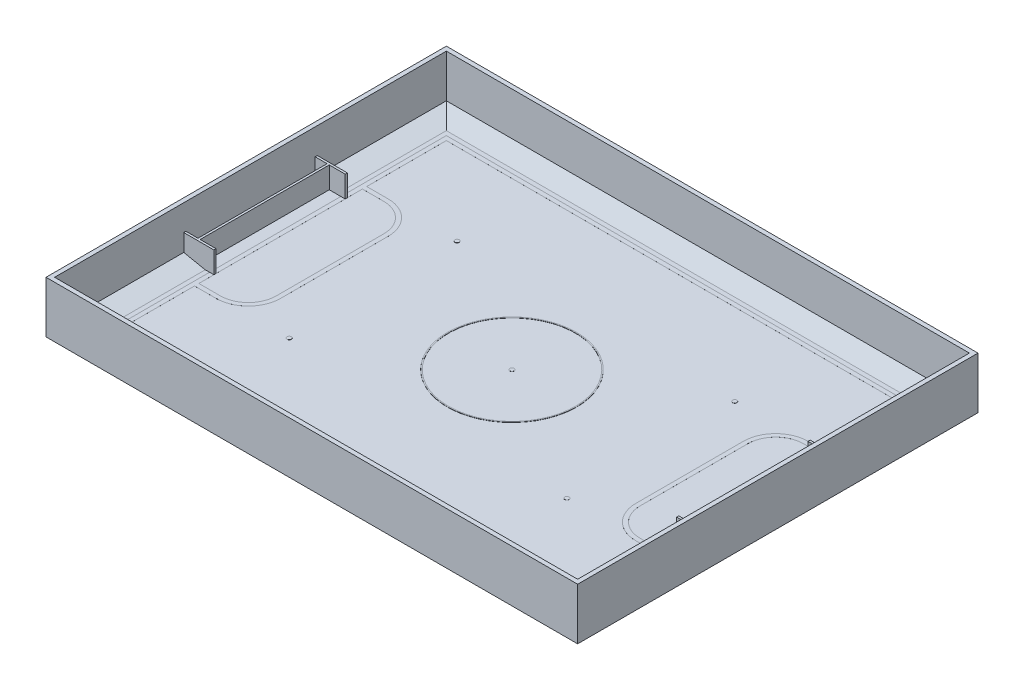
SolidWorks part; units mm, degrees
ref_plane "Alzado" through (0, 0, 0) normal (0, 0, 1) x (1, 0, 0)
ref_plane "Planta" through (0, 0, 0) normal (0, 1, 0) x (1, 0, 0)
ref_plane "Vista lateral" through (0, 0, 0) normal (1, 0, 0) x (0, 0, -1)
sketch "Croquis1" plane through (0, 0, 0) normal (0, 1, 0) x (1, 0, 0)
  line L0 (0, 0) -> (0, 182)
  line L1 (0, 182) -> (243, 182)
  line L2 (243, 182) -> (243, 0)
  line L3 (243, 0) -> (0, 0)
  line L4 (245, -2) -> (-2, -2)
  line L5 (-2, -2) -> (-2, 184)
  line L6 (-2, 184) -> (245, 184)
  line L7 (245, 184) -> (245, -2)
  dimension "D1" = 182
  dimension "D2" = 243
  dimension "D3" = 2
extrude "Wall" add sketch "Croquis1" along normal blind 24
sketch "Croquis4" plane through (0, 0, 0) normal (0, 1, 0) x (1, 0, 0)
  line L1 (243, 182) -> (0, 182)
  line L2 (243, 182) -> (243, 0)
  line L3 (243, 0) -> (0, 0)
  line L4 (0, 182) -> (0, 0)
extrude "Field" add sketch "Croquis4" along normal blind 2
sketch "Croquis5" plane through (0, 2, 0) normal (0, 1, 0) x (1, 0, 0)
  line L0 (243, 0) -> (231, 0) construction
  line L1 (0, 0) -> (243, 0) construction
  line L2 (231, 0) -> (231, 12) construction
  line L3 (231, 12) -> (12, 12)
  line L4 (12, 12) -> (12, 170)
  line L5 (12, 170) -> (231, 170)
  line L6 (231, 170) -> (231, 12)
  line L7 (229, 0) -> (229, 12)
  line L8 (229, 14) -> (14, 14)
  line L9 (14, 14) -> (14, 51)
  line L10 (14, 168) -> (229, 168)
  line L11 (229, 168) -> (229, 131)
  line L12 (229, 91) -> (204, 91) construction
  line L13 (204, 91) -> (204, 66)
  line L14 (219, 51) -> (229, 51)
  line L15 (204, 91) -> (206, 91) construction
  line L16 (219, 53) -> (229, 53)
  line L17 (206, 89) -> (206, 66)
  line L18 (206, 89) -> (206, 89)
  line L19 (206, 89) -> (206, 93)
  line L20 (121.5, 168) -> (121.5, 14) construction
  line L21 (204, 91) -> (206, 91) construction
  line L22 (206, 93) -> (206, 116)
  line L23 (219, 129) -> (229, 129)
  line L24 (219, 131) -> (229, 131)
  line L25 (204, 91) -> (204, 116)
  line L26 (39, 91) -> (37, 91) construction
  line L27 (39, 91) -> (37, 91) construction
  line L28 (14, 91) -> (39, 91) construction
  line L29 (39, 91) -> (39, 116)
  line L30 (24, 131) -> (14, 131)
  line L31 (24, 129) -> (14, 129)
  line L32 (37, 93) -> (37, 116)
  line L33 (37, 89) -> (37, 93)
  line L34 (37, 89) -> (37, 66)
  line L35 (24, 53) -> (14, 53)
  line L36 (24, 51) -> (14, 51)
  line L37 (39, 91) -> (39, 66)
  line L38 (14, 53) -> (14, 129)
  line L39 (14, 131) -> (14, 168)
  line L40 (14, 14) -> (14, 168) construction
  line L41 (229, 51) -> (229, 14)
  line L42 (229, 129) -> (229, 53)
  line L43 (229, 168) -> (229, 14) construction
  arc A0 (219, 51) -> (204, 66) centre (219, 66) cw
  arc A1 (219, 53) -> (206, 66) centre (219, 66) cw
  arc A2 (219, 129) -> (206, 116) centre (219, 116) ccw
  arc A3 (219, 131) -> (204, 116) centre (219, 116) ccw
  arc A4 (24, 131) -> (39, 116) centre (24, 116) cw
  arc A5 (24, 129) -> (37, 116) centre (24, 116) cw
  arc A6 (24, 53) -> (37, 66) centre (24, 66) ccw
  arc A7 (24, 51) -> (39, 66) centre (24, 66) ccw
  point P21 (204, 51)
  point P31 (204, 131)
  point P43 (39, 131)
  point P54 (39, 51)
  dimension "D8" = 15
  dimension "D1" = 158
  dimension "D2" = 219
  dimension "D3" = 12
  dimension "D4" = 12
  dimension "D5" = 2
  dimension "D6" = 40
  dimension "D7" = 25
  dimension "D9" = 2
extrude "WhiteLine" add sketch "Croquis5" along normal blind 0.01 contours L6 L5 L4 L3 L10 L11 L8 L9
sketch "Croquis6" plane through (0, 2, 0) normal (0, 1, 0) x (1, 0, 0)
  line L0 (14, 91) -> (229, 91) construction
  line L1 (14, 53) -> (14, 129) construction
  line L2 (229, 129) -> (229, 53) construction
  line L3 (12, 170) -> (57, 170) construction
  line L4 (12, 170) -> (231, 170) construction
  line L5 (57, 170) -> (57, 130) construction
  line L6 (14, 168) -> (229, 168) construction
  line L7 (121.5, 168) -> (121.5, 14) construction
  line L8 (229, 14) -> (14, 14) construction
  circle A0 centre (121.5, 91) radius 30
  circle A1 centre (121.5, 91) radius 29.5
  circle A2 centre (57, 130) radius 1
  circle A3 centre (57, 52) radius 1
  circle A4 centre (186, 52) radius 1
  circle A5 centre (186, 130) radius 1
  dimension "D1" = 0.5
  dimension "D2" = 45
extrude "Neutralzone" add sketch "Croquis6" along normal blind 0.1
sketch "Croquis8" plane through (0, 2, 0) normal (0, 1, 0) x (1, 0, 0)
  line L0 (121.5, 168) -> (121.5, 14) construction
  line L1 (14, 168) -> (229, 168) construction
  line L2 (229, 14) -> (14, 14) construction
  circle A0 centre (121.5, 91) radius 1
extrude "NeutralSpot" add sketch "Croquis8" along normal blind 0.1
sketch "Croquis9" plane through (0, 2, 0) normal (0, 1, 0) x (1, 0, 0)
  line L0 (14, 91) -> (14, 121) construction
  line L1 (14, 53) -> (14, 129) construction
  line L2 (14, 53) -> (14, 129) construction
  line L3 (14, 121) -> (6.6, 121)
  line L4 (6.6, 121) -> (6.6, 91)
  line L5 (6.6, 91) -> (14, 91) construction
  line L6 (14, 122) -> (5.6, 122)
  line L7 (5.6, 121) -> (5.6, 91)
  line L8 (14, 122) -> (14, 121)
  line L9 (14, 60) -> (14, 61)
  line L10 (5.6, 61) -> (5.6, 91)
  line L11 (14, 60) -> (5.6, 60)
  line L12 (6.6, 61) -> (6.6, 91)
  line L13 (14, 61) -> (6.6, 61)
  line L14 (121.5, 170) -> (121.5, 12) construction
  line L15 (12, 170) -> (231, 170) construction
  line L16 (231, 12) -> (12, 12) construction
  line L17 (236.4, 91) -> (229, 91) construction
  line L18 (229, 91) -> (229, 121) construction
  line L19 (229, 61) -> (236.4, 61)
  line L20 (236.4, 61) -> (236.4, 91)
  line L21 (229, 60) -> (237.4, 60)
  line L22 (237.4, 61) -> (237.4, 91)
  line L23 (229, 60) -> (229, 61)
  line L24 (229, 122) -> (229, 121)
  line L25 (237.4, 121) -> (237.4, 91)
  line L26 (229, 122) -> (237.4, 122)
  line L27 (236.4, 121) -> (236.4, 91)
  line L28 (229, 121) -> (236.4, 121)
  line L29 (5.6, 122) -> (0, 122)
  line L30 (0, 182) -> (0, 0) construction
  line L31 (0, 122) -> (0, 121)
  line L32 (0, 182) -> (0, 0) construction
  line L33 (0, 121) -> (5.6, 121)
  line L34 (5.6, 60) -> (0, 60)
  line L35 (5.6, 122) -> (5.6, 91) construction
  line L36 (0, 60) -> (0, 61)
  line L37 (0, 61) -> (5.6, 61)
  line L38 (237.4, 60) -> (243, 60)
  line L39 (243, 0) -> (243, 182) construction
  line L40 (243, 60) -> (243, 61)
  line L41 (243, 0) -> (243, 182) construction
  line L42 (243, 61) -> (237.4, 61)
  line L43 (237.4, 122) -> (243, 122)
  line L44 (243, 122) -> (243, 121)
  line L45 (243, 121) -> (237.4, 121)
  dimension "D1" = 1
extrude "Goals" add sketch "Croquis9" along normal blind 10
sketch "Croquis10" plane through (0, 0, 0) normal (1, 0, 0) x (0, 0, -1)
  line L0 (0, 2) -> (10, 2)
  line L1 (182, 2) -> (122, 2) construction
  line L4 (0, 4) -> (0, 2)
  line L5 (0, 4) -> (10, 2)
  line L6 (91, 24) -> (91, 9.8844) construction
  line L7 (182, 24) -> (0, 24) construction
  line L8 (182, 4) -> (172, 2)
  line L9 (182, 4) -> (182, 2)
  line L10 (182, 2) -> (172, 2)
extrude "Wedge1" add sketch "Croquis10" along normal blind 243
sketch "Croquis11" plane through (0, 0, 0) normal (0, 0, -1) x (-1, 0, 0)
  line L0 (0, 4) -> (0, 2)
  line L1 (0, 2) -> (-10, 2)
  line L2 (-10, 2) -> (0, 4)
  line L3 (-121.5, 24) -> (-121.5, 18.7224) construction
  line L4 (0, 24) -> (-243, 24) construction
  line L5 (-233, 2) -> (-243, 4)
  line L6 (-243, 2) -> (-233, 2)
  line L7 (-243, 4) -> (-243, 2)
extrude "Wedge2" add sketch "Croquis11" along normal blind 60
sketch "Croquis12" plane through (0, 0, -182) normal (0, 0, 1) x (1, 0, 0)
  line L0 (0, 4) -> (0, 2)
  line L1 (0, 2) -> (10, 2)
  line L2 (10, 2) -> (0, 4)
  line L3 (121.5, 24) -> (121.5, 19.8037) construction
  line L4 (243, 24) -> (0, 24) construction
  line L5 (233, 2) -> (243, 4)
  line L6 (243, 2) -> (233, 2)
  line L7 (243, 4) -> (243, 2)
extrude "Wedge3" add sketch "Croquis12" along normal blind 60
